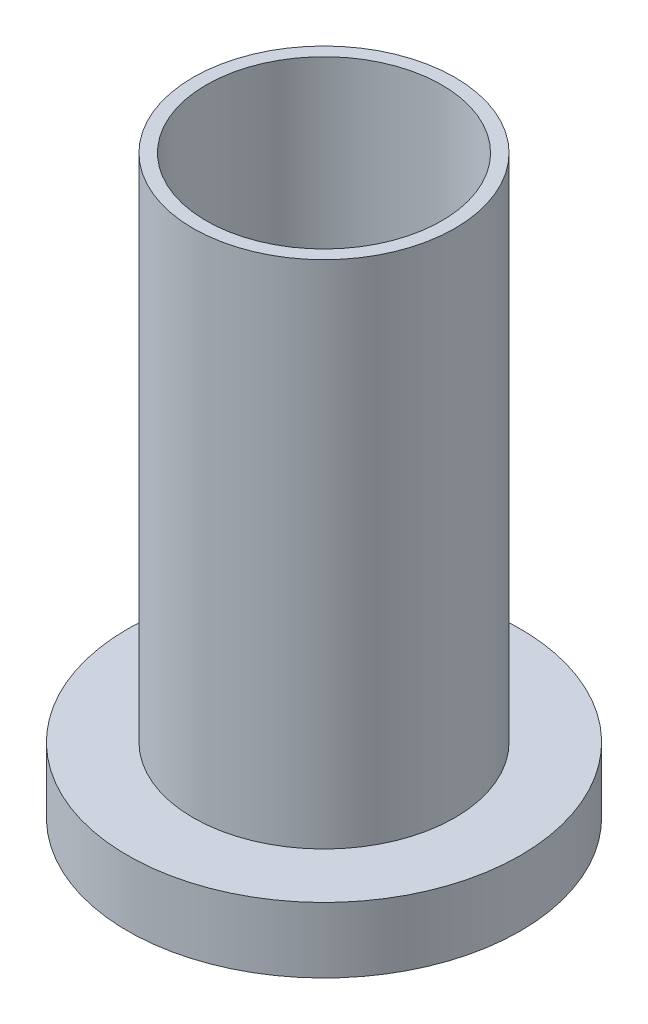
SolidWorks part; units mm, degrees
ref_plane "正面" through (0, 0, 0) normal (0, 0, 1) x (1, 0, 0)
ref_plane "平面" through (0, 0, 0) normal (0, 1, 0) x (1, 0, 0)
ref_plane "右側面" through (0, 0, 0) normal (1, 0, 0) x (0, 0, -1)
sketch "ｽｹｯﾁ1" plane through (0, 0, 0) normal (0, 0, 1) x (1, 0, 0)
  line L0 (0, 0) -> (0, 0.5)
  line L1 (0, 0.5) -> (0.5, 0.5)
  line L2 (0.5, 0.5) -> (0.5, 4.4)
  line L3 (0.5, 4.4) -> (1.5, 4.4)
  line L4 (1.5, 4.4) -> (1.5, 0)
  line L5 (1.5, 0) -> (0, 0)
  dimension "D1" = 0.5
  dimension "D2" = 1.5
  dimension "D3" = 3.9
  dimension "D4" = 1
revolve "回転1" add sketch "ｽｹｯﾁ1" angle 360 about L4
sketch "ｽｹｯﾁ2" plane through (0, 4.4, 0) normal (0, 1, 0) x (1, 0, 0)
  circle A0 centre (1.5, 0) radius 0.9
  dimension "D1" = 1.8
extrude "ｶｯﾄ - 押し出し1" cut sketch "ｽｹｯﾁ2" against normal offset from surface (3.9 mm away) 0.5 up to face at (0, 0, 0)
sketch "ｽｹｯﾁ3" [suppressed] plane through (0, 0, 0) normal (0, 0, 1) x (1, 0, 0)
  line L0 (0, 0) -> (0, 0.5)
  line L1 (0, 0.5) -> (0.7, 0.5)
  line L2 (0.7, 0.5) -> (0.7, 4.4)
  line L3 (0.7, 4.4) -> (1.5, 4.4)
  line L4 (1.5, 4.4) -> (1.5, 0)
  line L5 (1.5, 0) -> (0, 0)
  dimension "D1" = 0.5
  dimension "D2" = 1.5
  dimension "D3" = 3.9
  dimension "D4" = 0.8
revolve "回転2" [suppressed] add sketch "ｽｹｯﾁ3" angle 360 about L4
